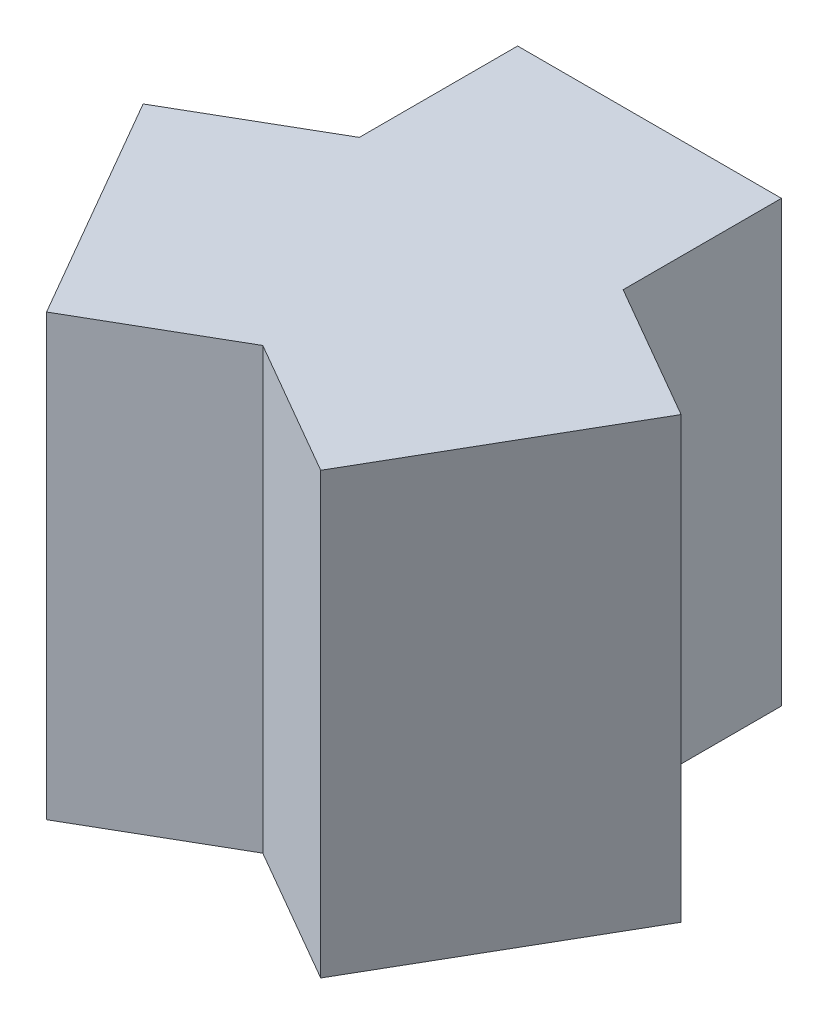
SolidWorks part; units mm, degrees
ref_plane "Front Plane" through (0, 0, 0) normal (0, 0, 1) x (1, 0, 0)
ref_plane "Top Plane" through (0, 0, 0) normal (0, 1, 0) x (1, 0, 0)
ref_plane "Right Plane" through (0, 0, 0) normal (1, 0, 0) x (0, 0, -1)
sketch "Sketch1" plane through (0, 0, 0) normal (0, 1, 0) x (1, 0, 0)
  line L0 (15.2942, 0.5) -> (7.5, 5)
  line L1 (7.5, 5) -> (7.5, 14)
  line L5 (0, -7.9904) -> (7.7942, -12.4904)
  line L7 (7.5, 5) -> (0, -7.9904) construction
  line L8 (7.5, 5) -> (-7.5, 5) construction
  line L9 (-7.5, 14) -> (7.5, 14)
  line L10 (15.2942, 0.5) -> (7.7942, -12.4904)
  line L12 (0, 30.0328) -> (0, -20.7177) construction
  line L13 (-7.5, 5) -> (0, -7.9904) construction
  line L14 (-15.2942, 0.5) -> (-7.7942, -12.4904)
  line L15 (0, -7.9904) -> (-7.7942, -12.4904)
  line L16 (-15.2942, 0.5) -> (-7.5, 5)
  line L17 (-7.5, 5) -> (-7.5, 14)
  point P6 (0, 5)
  point P9 (0, 14)
  dimension "D3" = 15
  dimension "D4" = 9
  dimension "D5" = 9
extrude "Boss-Extrude1" add sketch "Sketch1" along normal mid plane 25
